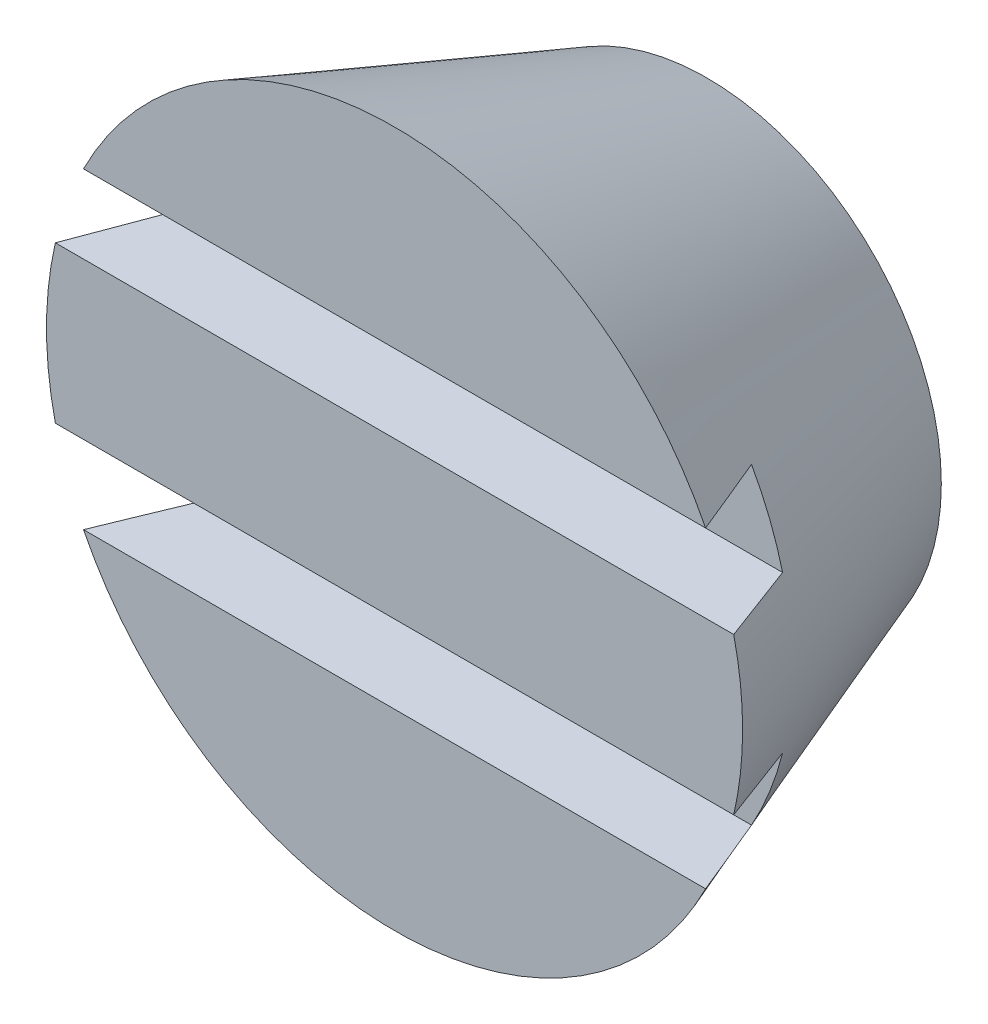
SolidWorks part; units mm, degrees
ref_plane "Plan de face" through (0, 0, 0) normal (0, 0, 1) x (1, 0, 0)
ref_plane "Plan de dessus" through (0, 0, 0) normal (0, 1, 0) x (1, 0, 0)
ref_plane "Plan de droite" through (0, 0, 0) normal (1, 0, 0) x (0, 0, -1)
sketch "Esquisse1" plane through (0, 0, 0) normal (0, 0, 1) x (1, 0, 0)
  circle A0 centre (0, 0) radius 15
  dimension "D1" = 30
extrude "Boss.-Extru.1" add sketch "Esquisse1" along normal blind 20 draft 20 draft outward yes
sketch "Esquisse2" plane through (0, 0, 20) normal (0, 0, 1) x (1, 0, 0)
  line L0 (0, 0) -> (-22.2794, 0) construction
  line L1 (24.6297, -10) -> (-24.6297, -10)
  line L2 (24.6297, -10) -> (24.6297, -5)
  line L3 (24.6297, -5) -> (-24.6297, -5)
  line L4 (-24.6297, -10) -> (-24.6297, -5)
  line L5 (24.6297, -10) -> (-24.6297, -5) construction
  line L6 (24.6297, -5) -> (-24.6297, -10) construction
  line L7 (24.6297, 5) -> (-24.6297, 10) construction
  line L8 (24.6297, 10) -> (-24.6297, 5) construction
  line L9 (-24.6297, 10) -> (-24.6297, 5)
  line L10 (24.6297, 5) -> (-24.6297, 5)
  line L11 (24.6297, 10) -> (24.6297, 5)
  line L12 (24.6297, 10) -> (-24.6297, 10)
  circle A0 centre (0, 0) radius 22.2794 construction
  point P0 (0, -7.5)
  point P14 (0, 7.5)
  dimension "D1" = 5
  dimension "D2" = 10
extrude "Enlèv. mat.-Extru.1" cut sketch "Esquisse2" against normal blind 5
